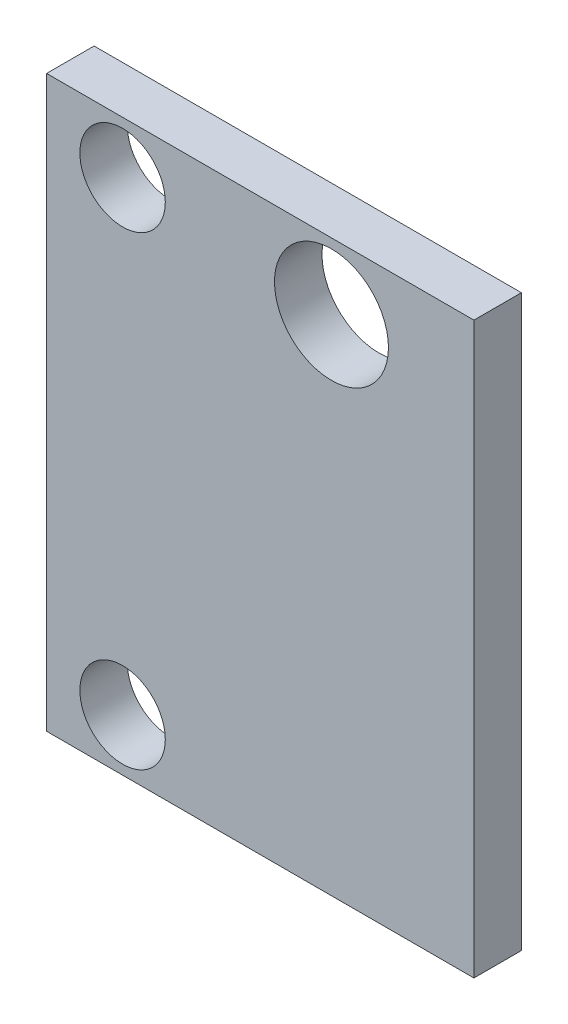
SolidWorks part; units mm, degrees
ref_plane "Płaszczyzna przednia" through (0, 0, 0) normal (0, 0, 1) x (1, 0, 0)
ref_plane "Płaszczyzna górna" through (0, 0, 0) normal (0, 1, 0) x (1, 0, 0)
ref_plane "Płaszczyzna prawa" through (0, 0, 0) normal (1, 0, 0) x (0, 0, -1)
sketch "Szkic1" plane through (0, 0, 0) normal (0, 0, 1) x (1, 0, 0)
  line L0 (0, 0) -> (-28.2296, 0) construction
  line L1 (-22.5, -30) -> (22.5, -30)
  line L2 (-22.5, -30) -> (-22.5, 30)
  line L3 (-22.5, 30) -> (22.5, 30)
  line L4 (22.5, -30) -> (22.5, 30)
  line L5 (-22.5, -30) -> (22.5, 30) construction
  line L6 (-22.5, 30) -> (22.5, -30) construction
  circle A0 centre (-14.5, 24.5) radius 4.5
  circle A1 centre (-14.5, -24.5) radius 4.5
  point P0 (0, 0)
  dimension "D3" = 9
  dimension "D1" = 45
  dimension "D2" = 60
  dimension "D4" = 49
  dimension "D5" = 8
extrude "Dodanie-wyciągnięcie1" add sketch "Szkic1" along normal blind 5
sketch "Szkic2" plane through (0, 0, 5) normal (0, 0, 1) x (1, 0, 0)
  line L0 (22.5, 30) -> (-22.5, 30) construction
  line L1 (22.5, -30) -> (22.5, 30) construction
  circle A0 centre (7.5, 23) radius 6
  dimension "D1" = 7
  dimension "D3" = 12
  dimension "D2" = 15
extrude "Wytnij-wyciągnięcie1" cut sketch "Szkic2" against normal blind 10
